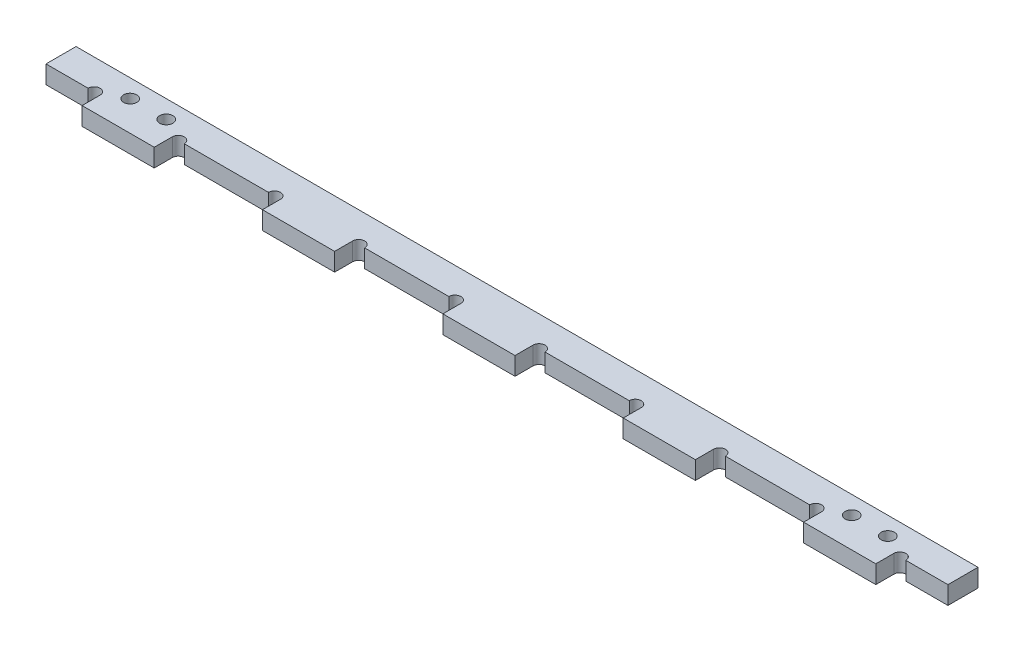
SolidWorks part; units mm, degrees
material "玻纤板"
ref_plane "前视基准面" through (0, 0, 0) normal (0, 0, 1) x (1, 0, 0)
ref_plane "上视基准面" through (0, 0, 0) normal (0, 1, 0) x (1, 0, 0)
ref_plane "右视基准面" through (0, 0, 0) normal (1, 0, 0) x (0, 0, -1)
sketch "草图1" plane through (0, 0, 0) normal (0, 1, 0) x (1, 0, 0)
  line L1 (-75, -2.5) -> (75, -2.5)
  line L2 (-75, -2.5) -> (-75, 2.5)
  line L3 (-75, 2.5) -> (75, 2.5)
  line L4 (75, -2.5) -> (75, 2.5)
  line L5 (0, 2.5) -> (0, -2.5) construction
  line L6 (-75, 0) -> (75, 0) construction
  point P0 (0, 0)
  dimension "D1" = 5
  dimension "D2" = 150
extrude "凸台-拉伸1" add sketch "草图1" along normal mid plane 3
sketch "草图2" plane through (0, 1.5, 0) normal (0, 1, 0) x (1, 0, 0)
  line L0 (-75, -2.5) -> (75, -2.5) construction
  line L1 (-66, -2.5) -> (-54, -2.5)
  line L2 (-66, -2.5) -> (-66, -5.5)
  line L3 (-66, -5.5) -> (-54, -5.5)
  line L4 (-54, -2.5) -> (-54, -5.5)
  line L5 (-60, -5.5) -> (-60, -2.5) construction
  line L6 (-66, -4) -> (-54, -4) construction
  line L7 (-36, -2.5) -> (-36, -5.5)
  line L8 (-36, -2.5) -> (-24, -2.5)
  line L9 (-24, -2.5) -> (-24, -5.5)
  line L10 (-36, -5.5) -> (-24, -5.5)
  line L11 (-6, -2.5) -> (-6, -5.5)
  line L12 (-6, -2.5) -> (6, -2.5)
  line L13 (6, -2.5) -> (6, -5.5)
  line L14 (-6, -5.5) -> (6, -5.5)
  line L15 (24, -2.5) -> (24, -5.5)
  line L16 (24, -2.5) -> (36, -2.5)
  line L17 (36, -2.5) -> (36, -5.5)
  line L18 (24, -5.5) -> (36, -5.5)
  line L19 (54, -2.5) -> (54, -5.5)
  line L20 (54, -2.5) -> (66, -2.5)
  line L21 (66, -2.5) -> (66, -5.5)
  line L22 (54, -5.5) -> (66, -5.5)
  point P248 (-60, -4)
  dimension "D1" = 12
  dimension "D2" = 3
  dimension "D3" = 60
  dimension "D5" = 18
  dimension "D4" = 5
extrude "凸台-拉伸2" add sketch "草图2" against normal up to surface (3 mm away) up to face at (0, -1.5, 0)
sketch "草图3" plane through (0, -1.5, 0) normal (0, -1, 0) x (1, 0, 0)
  line L0 (66, 2.5) -> (75, 2.5) construction
  line L1 (60, 5.5) -> (60, -2.5) construction
  line L2 (54, 5.5) -> (66, 5.5) construction
  line L3 (75, -2.5) -> (-75, -2.5) construction
  circle A0 centre (67, 2.5) radius 1
  circle A1 centre (53, 2.5) radius 1
  circle A2 centre (37, 2.5) radius 1
  circle A3 centre (23, 2.5) radius 1
  circle A4 centre (7, 2.5) radius 1
  circle A5 centre (-7, 2.5) radius 1
  circle A6 centre (-23, 2.5) radius 1
  circle A7 centre (-37, 2.5) radius 1
  circle A8 centre (-53, 2.5) radius 1
  circle A9 centre (-67, 2.5) radius 1
  dimension "D2" = 30
  dimension "D3" = 2
  dimension "D1" = 5
extrude "切除-拉伸1" cut sketch "草图3" against normal through all
sketch "草图4" plane through (0, 1.5, 0) normal (0, 1, 0) x (1, 0, 0)
  line L0 (75, -0.5) -> (0, -0.5) construction
  line L1 (75, -2.5) -> (75, 2.5) construction
  line L2 (0, -0.5) -> (0, 0) construction
  line L3 (75, 2.5) -> (-75, 2.5) construction
  line L4 (60, -5.5) -> (60, -0.5) construction
  line L5 (54, -5.5) -> (66, -5.5) construction
  circle A0 centre (63, -0.5) radius 1.1
  circle A1 centre (57, -0.5) radius 1.1
  circle A2 centre (-57, -0.5) radius 1.1
  circle A3 centre (-63, -0.5) radius 1.1
  dimension "D2" = 2.2
  dimension "D1" = 3
  dimension "D3" = 6
extrude "切除-拉伸2" cut sketch "草图4" against normal through all
